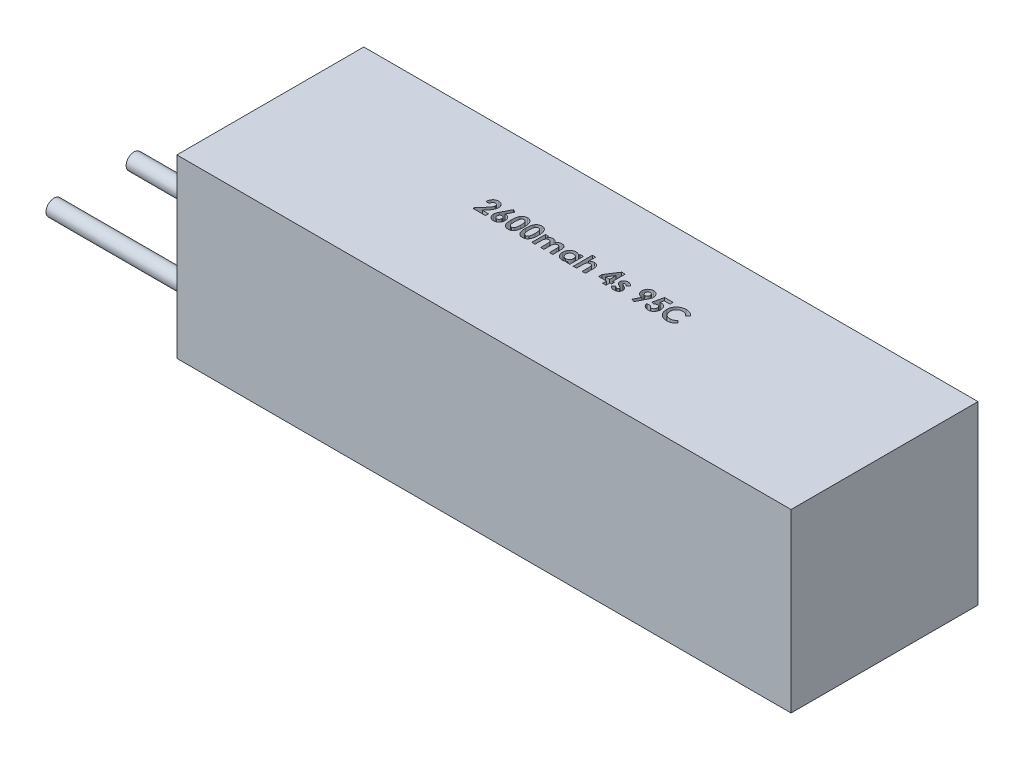
SolidWorks part; units mm, degrees
ref_plane "前视基准面" through (0, 0, 0) normal (0, 0, 1) x (1, 0, 0)
ref_plane "上视基准面" through (0, 0, 0) normal (0, 1, 0) x (1, 0, 0)
ref_plane "右视基准面" through (0, 0, 0) normal (1, 0, 0) x (0, 0, -1)
sketch "草图1" plane through (0, 0, 0) normal (0, 1, 0) x (1, 0, 0)
  line L1 (-57.5, 17.5) -> (57.5, 17.5)
  line L2 (-57.5, 17.5) -> (-57.5, -17.5)
  line L3 (-57.5, -17.5) -> (57.5, -17.5)
  line L4 (57.5, 17.5) -> (57.5, -17.5)
  line L5 (-57.5, 17.5) -> (57.5, -17.5) construction
  line L6 (-57.5, -17.5) -> (57.5, 17.5) construction
  point P0 (0, 0)
  dimension "D1" = 115
  dimension "D2" = 35
extrude "凸台-拉伸1" add sketch "草图1" along normal blind 33
sketch "草图2" plane through (-57.5, 0, 0) normal (-1, 0, 0) x (0, 0, 1)
  line L0 (-17.5, 0) -> (17.5, 0) construction
  circle A0 centre (-7.5, 3) radius 1.5
  circle A1 centre (7.5, 3) radius 1.5
  point P7 (0, 0)
  dimension "D1" = 3
  dimension "D2" = 15
  dimension "D3" = 7.5
  dimension "D4" = 3
extrude "凸台-拉伸2" add sketch "草图2" along normal blind 33
sketch "草图3" plane through (0, 33, 0) normal (0, 1, 0) x (1, 0, 0)
  text T0 "<b>2600mah 4s 95C</b>" font "Century Gothic" height 3.5
extrude "切除-拉伸1" cut sketch "草图3" against normal blind 5
